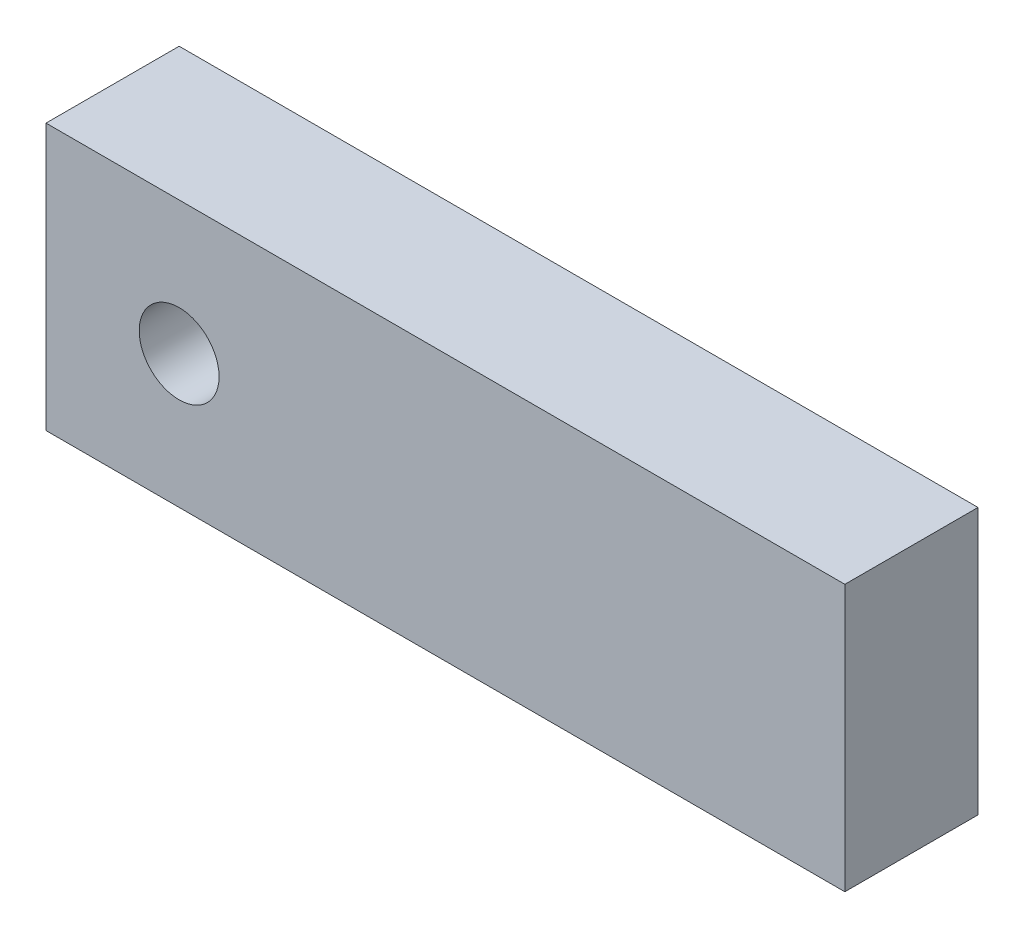
SolidWorks part; units mm, degrees
ref_plane "Front" through (0, 0, 0) normal (0, 0, 1) x (1, 0, 0)
ref_plane "Top" through (0, 0, 0) normal (0, 1, 0) x (1, 0, 0)
ref_plane "Right" through (0, 0, 0) normal (1, 0, 0) x (0, 0, -1)
sketch "Sketch1" plane through (0, 0, 0) normal (0, 0, 1) x (1, 0, 0)
  line L1 (-15, 5) -> (15, 5)
  line L2 (-15, 5) -> (-15, -5)
  line L3 (-15, -5) -> (15, -5)
  line L4 (15, 5) -> (15, -5)
  line L5 (-15, 5) -> (15, -5) construction
  line L6 (-15, -5) -> (15, 5) construction
  point P0 (0, 0)
extrude "Boss-Extrude1" add sketch "Sketch1" along normal blind 5
sketch "Sketch2" plane through (0, 0, 5) normal (0, 0, 1) x (1, 0, 0)
  circle A0 centre (-10, 0) radius 1.5
extrude "Cut-Extrude1" cut sketch "Sketch2" against normal blind 5
